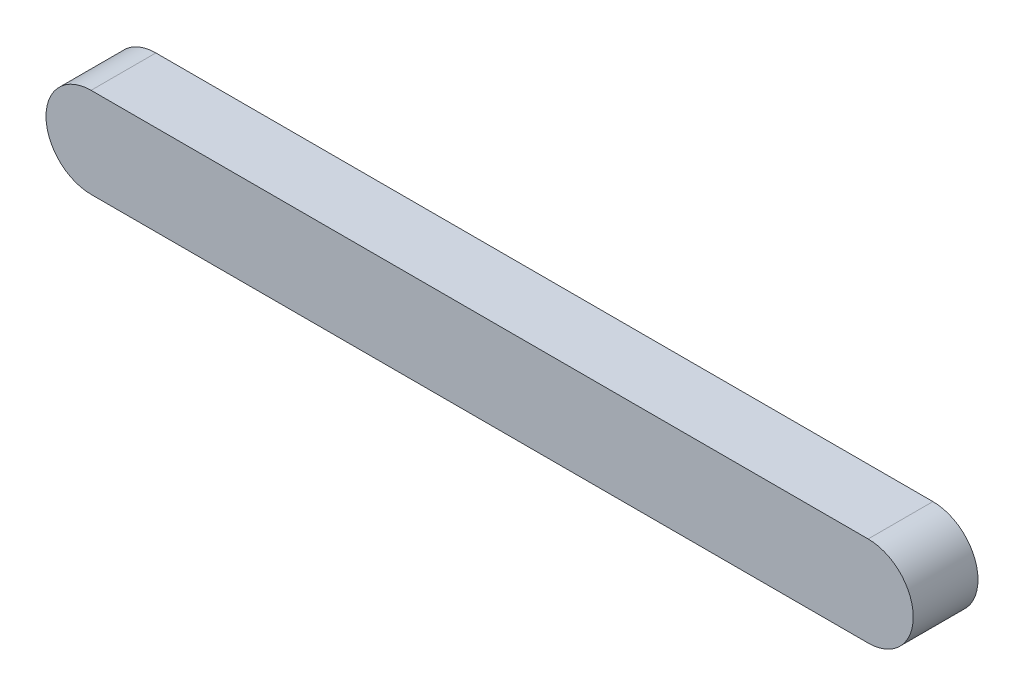
SolidWorks part; units mm, degrees
ref_plane "前视基准面" through (0, 0, 0) normal (0, 0, 1) x (1, 0, 0)
ref_plane "上视基准面" through (0, 0, 0) normal (0, 1, 0) x (1, 0, 0)
ref_plane "右视基准面" through (0, 0, 0) normal (1, 0, 0) x (0, 0, -1)
other "Configuration Table"
sketch "草图1" plane through (0, 0, 0) normal (0, 0, 1) x (1, 0, 0)
  line L0 (0, 0) -> (120, 0) construction
  line L3 (0, 6.9628) -> (120, 6.9628)
  line L4 (0, -6.9628) -> (120, -6.9628)
  arc A2 (0, 6.9628) -> (0, -6.9628) centre (0, 0) ccw
  arc A3 (120, -6.9628) -> (120, 6.9628) centre (120, 0) ccw
  point P2 (60, 0)
  dimension "D1" = 120
  dimension "D2" = 13.9256
extrude "凸台-拉伸1" add sketch "草图1" along normal blind 10
